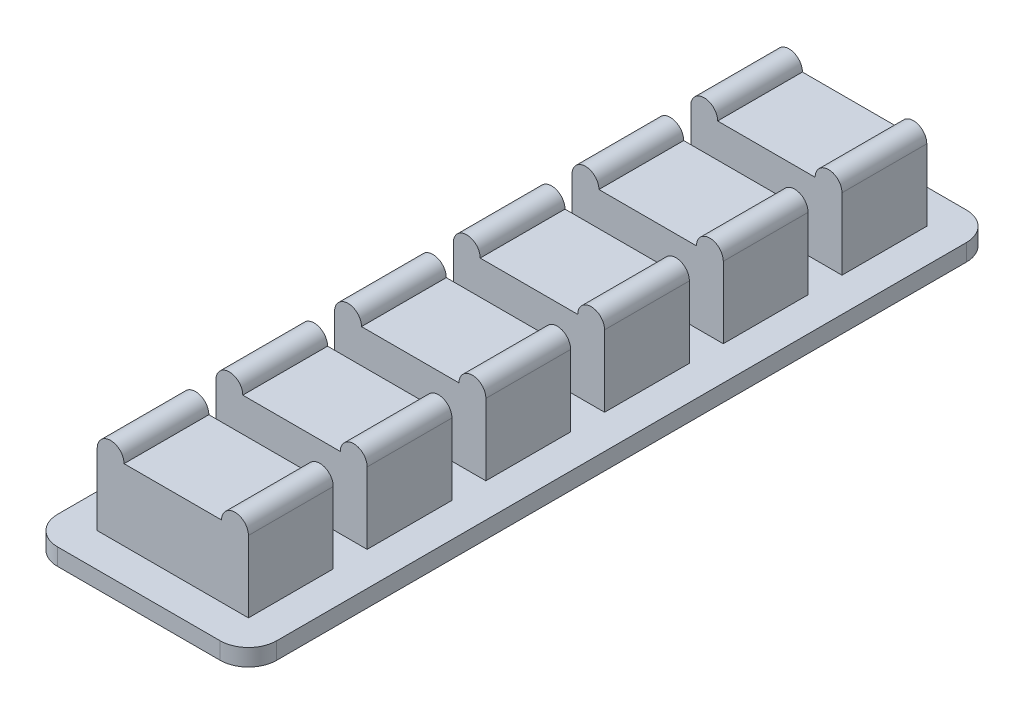
SolidWorks part; units mm, degrees
ref_plane "Front Plane" through (0, 0, 0) normal (0, 0, 1) x (1, 0, 0)
ref_plane "Top Plane" through (0, 0, 0) normal (0, 1, 0) x (1, 0, 0)
ref_plane "Right Plane" through (0, 0, 0) normal (1, 0, 0) x (0, 0, -1)
sketch "Sketch2" plane through (0, 0, 0) normal (0, 1, 0) x (1, 0, 0)
  line L0 (-31.007, 48) -> (134.6932, 48) construction
  line L1 (10, 0) -> (67.5, 0)
  line L2 (0, 10) -> (0, 254)
  line L3 (10, 264) -> (67.5, 264)
  line L4 (77.5, 10) -> (77.5, 254)
  line L13 (-37.3294, 90) -> (127.0536, 90) construction
  line L18 (-27.5824, 132) -> (189.2242, 132) construction
  arc A0 (67.5, 264) -> (77.5, 254) centre (67.5, 254) cw
  arc A1 (10, 264) -> (0, 254) centre (10, 254) ccw
  arc A2 (67.5, 0) -> (77.5, 10) centre (67.5, 10) ccw
  arc A3 (10, 0) -> (0, 10) centre (10, 10) cw
  point P17 (0, 0)
  dimension "D1" = 10
  dimension "D8" = 216.8065
extrude "Boss-Extrude1" add sketch "Sketch2" along normal blind 6
sketch "Sketch3" plane through (0, 6, 0) normal (0, 1, 0) x (1, 0, 0)
  line L0 (10, 0) -> (67.5, 0) construction
  line L1 (12, 42) -> (65.5, 42)
  line L2 (12, 42) -> (12, 12)
  line L3 (12, 12) -> (65.5, 12)
  line L4 (65.5, 42) -> (65.5, 12)
  line L5 (0, 254) -> (0, 10) construction
  line L6 (-31.8507, 48) -> (119.0782, 48) construction
  line L7 (12, 84) -> (65.5, 84)
  line L8 (65.5, 54) -> (65.5, 84)
  line L9 (12, 54) -> (65.5, 54)
  line L10 (12, 54) -> (12, 84)
  line L11 (-89.99, 90) -> (60.9389, 90) construction
  line L12 (12, 126) -> (12, 96)
  line L13 (12, 126) -> (65.5, 126)
  line L14 (65.5, 126) -> (65.5, 96)
  line L15 (12, 96) -> (65.5, 96)
  line L16 (-50.342, 132) -> (100.5869, 132) construction
  line L17 (12, 252) -> (65.5, 252)
  line L18 (65.5, 222) -> (65.5, 252)
  line L19 (12, 222) -> (65.5, 222)
  line L20 (12, 222) -> (12, 252)
  line L21 (12, 210) -> (12, 180)
  line L22 (12, 210) -> (65.5, 210)
  line L23 (65.5, 210) -> (65.5, 180)
  line L24 (12, 180) -> (65.5, 180)
  line L25 (12, 138) -> (65.5, 138)
  line L26 (65.5, 138) -> (65.5, 168)
  line L27 (12, 168) -> (65.5, 168)
  line L28 (12, 138) -> (12, 168)
  dimension "D1" = 30
  dimension "D2" = 53.5
  dimension "D3" = 12
  dimension "D4" = 12
  dimension "D5" = 6
  dimension "D6" = 6
  dimension "D7" = 6
extrude "Boss-Extrude2" add sketch "Sketch3" along normal blind 30
sketch "Sketch4" plane through (0, 0, -12) normal (0, 0, 1) x (1, 0, 0)
  line L0 (12, 36) -> (12, 6) construction
  line L1 (12, 36) -> (65.5, 36) construction
  line L2 (65.5, 36) -> (65.5, 6) construction
  line L3 (12, 31.25) -> (12, 36)
  line L4 (21.5, 31.25) -> (56, 31.25)
  line L5 (21.5, 31.25) -> (21.5, 36)
  line L6 (21.5, 36) -> (56, 36)
  line L7 (56, 31.25) -> (56, 36)
  line L8 (12, 36) -> (16.75, 36)
  line L9 (60.75, 36) -> (65.5, 36)
  line L10 (65.5, 36) -> (65.5, 31.25)
  circle A0 centre (16.75, 31.25) radius 4.75
  circle A1 centre (60.75, 31.25) radius 4.75
  arc A2 (16.75, 36) -> (12, 31.25) centre (16.75, 31.25) ccw
  arc A3 (60.75, 36) -> (65.5, 31.25) centre (60.75, 31.25) cw
  line M4 (65.5, 6) -> (65.5, 36)
  line M5 (65.5, 36) -> (12, 36)
  dimension "D1" = 9.5
  dimension "D2" = 9.5
extrude "Cut-Extrude1" cut sketch "Sketch4" against normal blind 240 contours A0 L5 M5 | L4 L7 L5 M5 | A1 L7 M5 | A1 M4 M5 | L8 A2 L3
